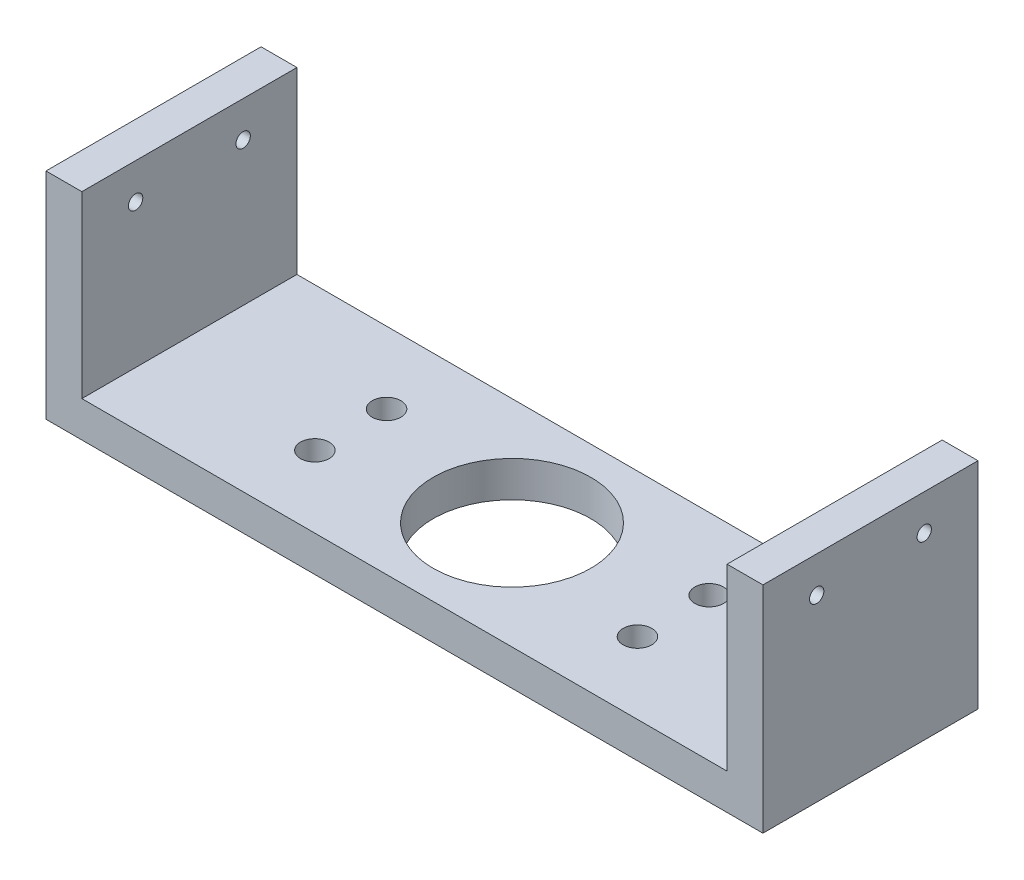
SolidWorks part; units mm, degrees
material "ABS"
ref_plane "Front Plane" through (0, 0, 0) normal (0, 0, 1) x (1, 0, 0)
ref_plane "Top Plane" through (0, 0, 0) normal (0, 1, 0) x (1, 0, 0)
ref_plane "Right Plane" through (0, 0, 0) normal (1, 0, 0) x (0, 0, -1)
sketch "Sketch2" plane through (0, 0, 0) normal (0, 1, 0) x (1, 0, 0)
  line L1 (-50, 15) -> (50, 15)
  line L2 (-50, 15) -> (-50, -15)
  line L3 (-50, -15) -> (50, -15)
  line L4 (50, 15) -> (50, -15)
  line L5 (-50, 15) -> (50, -15) construction
  line L6 (-50, -15) -> (50, 15) construction
  circle A0 centre (0, 0) radius 11
  dimension "D1" = 22
  dimension "D2" = 100
  dimension "D3" = 30
extrude "Boss-Extrude1" add sketch "Sketch2" along normal blind 5
sketch "Sketch3" plane through (0, 5, 0) normal (0, 1, 0) x (1, 0, 0)
  line L0 (-50, -15) -> (50, -15) construction
  line L1 (-50, 15) -> (-45, 15)
  line L2 (-50, 15) -> (-50, -15)
  line L3 (-50, -15) -> (-45, -15)
  line L4 (-45, 15) -> (-45, -15)
  line L6 (50, 15) -> (45, 15)
  line L7 (50, 15) -> (50, -15)
  line L8 (50, -15) -> (45, -15)
  line L9 (45, 15) -> (45, -15)
  dimension "D1" = 5
  dimension "D2" = 5
extrude "Boss-Extrude2" add sketch "Sketch3" along normal blind 25
sketch "Sketch4" plane through (50, 0, 0) normal (1, 0, 0) x (0, 0, -1)
  line L0 (-7.5, 25) -> (7.5, 25) construction
  line L1 (0, 30) -> (0, 0) construction
  line L2 (-15, 30) -> (15, 30) construction
  line L3 (-15, 0) -> (15, 0) construction
  circle A0 centre (-7.5, 25) radius 1
  circle A1 centre (7.5, 25) radius 1
  point P11 (0, 25)
  dimension "D2" = 2
  dimension "D3" = 2
  dimension "D1" = 15
  dimension "D4" = 5
extrude "Cut-Extrude1" cut sketch "Sketch4" against normal through all
sketch "Sketch5" plane through (0, 0, 0) normal (0, -1, 0) x (1, 0, 0)
  line L0 (-22.5, -5) -> (22.5, -5) construction
  line L1 (50, -15) -> (-50, -15) construction
  line L2 (-50, 15) -> (50, 15) construction
  line L3 (0, 15) -> (0, -15) construction
  circle A0 centre (-22.5, -5) radius 2
  circle A1 centre (22.5, -5) radius 2
  circle A2 centre (-22.5, 5) radius 2
  circle A3 centre (22.5, 5) radius 2
  point P9 (0, -5)
  dimension "D2" = 4
  dimension "D3" = 4
  dimension "D4" = 4
  dimension "D5" = 4
  dimension "D1" = 45
  dimension "D6" = 10
  dimension "D7" = 10
extrude "Cut-Extrude2" cut sketch "Sketch5" against normal blind 10
